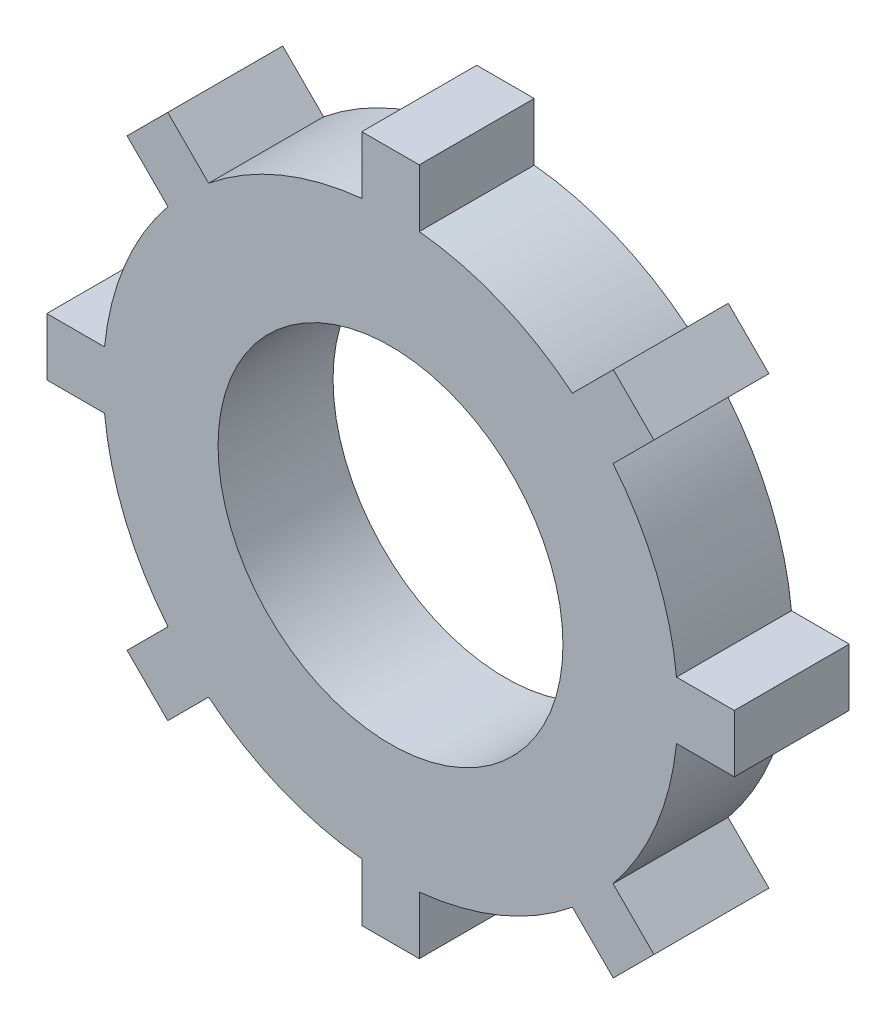
SolidWorks part; units mm, degrees
ref_plane "Front Plane" through (0, 0, 0) normal (0, 0, 1) x (1, 0, 0)
ref_plane "Top Plane" through (0, 0, 0) normal (0, 1, 0) x (1, 0, 0)
ref_plane "Right Plane" through (0, 0, 0) normal (1, 0, 0) x (0, 0, -1)
sketch "Sketch1" plane through (0, 0, 0) normal (0, 0, 1) x (1, 0, 0)
  line L0 (-47.7391, 0) -> (51.6234, 0) construction
  line L1 (0, 41.4307) -> (0, -35.0207) construction
  line L2 (-30.9469, -30.9469) -> (38.1517, 38.1517) construction
  line L3 (38.943, -38.943) -> (-39.8502, 39.8502) construction
  line L4 (22.9136, 19.378) -> (19.3568, 15.8213)
  line L5 (-2.5, 29.9) -> (2.5, 29.9)
  line L6 (-2.5, 29.9) -> (-2.5, 24.8747)
  line L7 (-2.5, -29.9) -> (2.5, -29.9)
  line L8 (2.5, 29.9) -> (2.5, 24.8747)
  line L9 (-29.9, 2.5) -> (-24.8747, 2.5)
  line L10 (-29.9, 2.5) -> (-29.9, -2.5)
  line L11 (-29.9, -2.5) -> (-24.8747, -2.5)
  line L12 (29.9, 2.5) -> (29.9, -2.5)
  line L14 (24.8747, 2.5) -> (29.9, 2.5)
  line L15 (24.8747, -2.5) -> (29.9, -2.5)
  line L16 (2.5, -24.8747) -> (2.5, -29.9)
  line L17 (-2.5, -24.8747) -> (-2.5, -29.9)
  line L18 (15.8213, 19.3568) -> (19.378, 22.9136)
  line L19 (19.378, 22.9136) -> (22.9136, 19.378)
  line L20 (-15.8213, -19.3568) -> (-19.378, -22.9136)
  line L21 (-19.378, -22.9136) -> (-22.9136, -19.378)
  line L22 (-22.9136, -19.378) -> (-19.3568, -15.8213)
  line L23 (19.3568, -15.8213) -> (22.9136, -19.378)
  line L24 (22.9136, -19.378) -> (19.378, -22.9136)
  line L25 (19.378, -22.9136) -> (15.8213, -19.3568)
  line L26 (-15.8213, 19.3568) -> (-19.378, 22.9136)
  line L27 (-19.378, 22.9136) -> (-22.9136, 19.378)
  line L28 (-22.9136, 19.378) -> (-19.3568, 15.8213)
  circle A0 centre (0, 0) radius 15
  arc A1 (-2.5, 24.8747) -> (-15.8213, 19.3568) centre (0, 0) ccw
  arc A2 (24.8747, 2.5) -> (19.3568, 15.8213) centre (0, 0) ccw
  arc A3 (2.5, -24.8747) -> (15.8213, -19.3568) centre (0, 0) ccw
  arc A4 (-24.8747, -2.5) -> (-19.3568, -15.8213) centre (0, 0) ccw
  arc A5 (15.8213, 19.3568) -> (2.5, 24.8747) centre (0, 0) ccw
  arc A6 (-15.8213, -19.3568) -> (-2.5, -24.8747) centre (0, 0) ccw
  arc A7 (19.3568, -15.8213) -> (24.8747, -2.5) centre (0, 0) ccw
  arc A8 (-19.3568, 15.8213) -> (-24.8747, 2.5) centre (0, 0) ccw
  dimension "D1" = 30
  dimension "D2" = 50
  dimension "D3" = 45
  dimension "D4" = 45
  dimension "D5" = 5
  dimension "D6" = 2.5
  dimension "D7" = 5
  dimension "D8" = 2.5
  dimension "D9" = 29.9
  dimension "D10" = 29.9
  dimension "D11" = 29.9
  dimension "D12" = 29.9
  dimension "D13" = 5
  dimension "D14" = 2.5
  dimension "D15" = 5
  dimension "D16" = 2.5
  dimension "D17" = 5.03
  dimension "D18" = 5
  dimension "D19" = 2.5
  dimension "D20" = 5.03
  dimension "D21" = 5
  dimension "D22" = 2.5
  dimension "D23" = 5.03
  dimension "D24" = 2.5
  dimension "D25" = 5.03
  dimension "D26" = 5
extrude "Boss-Extrude1" add sketch "Sketch1" along normal blind 10
